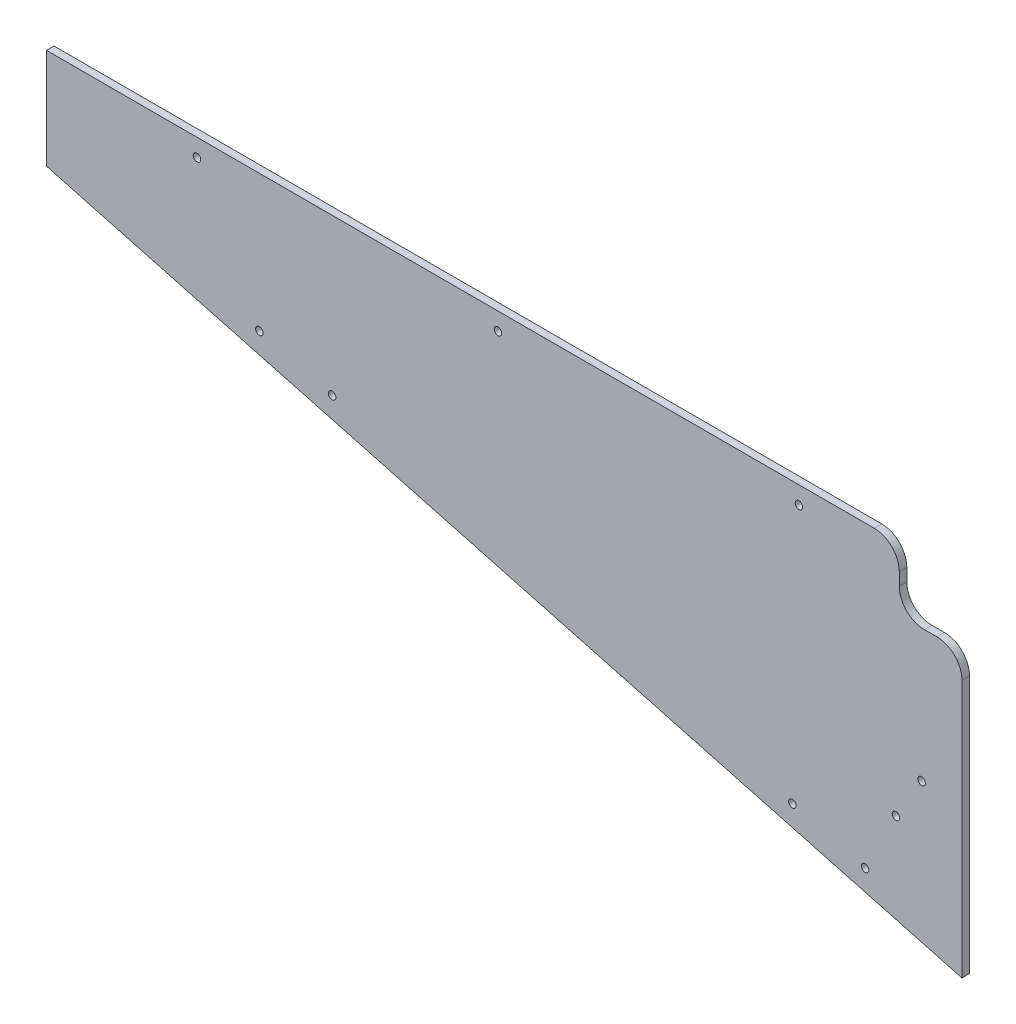
SolidWorks part; units mm, degrees
material "环氧树脂,未充填"
ref_plane "前视基准面" through (0, 0, 0) normal (0, 0, 1) x (1, 0, 0)
ref_plane "上视基准面" through (0, 0, 0) normal (0, 1, 0) x (1, 0, 0)
ref_plane "右视基准面" through (0, 0, 0) normal (1, 0, 0) x (0, 0, -1)
sketch "草图1" plane through (0, 0, 0) normal (0, 0, 1) x (1, 0, 0)
  line L0 (0, 0) -> (-514.282, 0)
  line L1 (-514.282, 0) -> (0, -137.8015)
  line L2 (0, -137.8015) -> (0, 0)
  line L3 (-365, 0) -> (-365, -40) construction
  line L4 (-365, 0) -> (-365, -40)
  dimension "D1" = 15
  dimension "D2" = 365
  dimension "D3" = 40
extrude "凸台-拉伸1" add sketch "草图1" along normal blind 3 contours L0 L4 L1 L2
sketch "草图3" plane through (0, 0, 3) normal (0, 0, 1) x (1, 0, 0)
  line L1 (0, 0) -> (-25, 0)
  line L2 (0, 0) -> (0, -25)
  line L3 (0, -25) -> (-25, -25)
  line L4 (-25, 0) -> (-25, -25)
  dimension "D1" = 25
  dimension "D2" = 25
extrude "切除-拉伸1" cut sketch "草图3" against normal through all
sketch "草图5" plane through (0, 0, 3) normal (0, 0, 1) x (1, 0, 0)
  line L0 (-376.077, -7) -> (-25, -7) construction
  line L2 (-25, 0) -> (-25, -25) construction
  line L3 (-25, 0) -> (-365, 0) construction
  circle A0 centre (-305, -7) radius 1.5
  circle A1 centre (-185, -7) radius 1.5
  circle A2 centre (-65, -7) radius 1.5
  dimension "D1" = 3
  dimension "D2" = 40
  dimension "D4" = 120
  dimension "D5" = 7
  dimension "D3" = 3
extrude "切除-拉伸3" cut sketch "草图5" against normal through all
fillet "圆角2" radius 10 3 edges at (0, -25, 1.5) (-25, -25, 1.5) (-25, 0, 1.5)
sketch "草图6" plane through (0, 0, 3) normal (0, 0, 1) x (1, 0, 0)
  line L0 (-483.3724, 0) -> (0, -129.5192) construction
  line L1 (-365, -40) -> (0, -137.8015) construction
  line L2 (0, -137.8015) -> (0, -35) construction
  line L3 (-35, 0) -> (-365, 0) construction
  circle A0 centre (-38.637, -119.1665) radius 1.5
  circle A1 centre (-67.6148, -111.4019) radius 1.5
  circle A2 centre (-251.1407, -62.2263) radius 1.5
  circle A3 centre (-280.1185, -54.4617) radius 1.5
  dimension "D2" = 30
  dimension "D3" = 3
  dimension "D5" = 30
  dimension "D1" = 8
  dimension "D4" = 40
  dimension "D6" = 190
extrude "切除-拉伸6" cut sketch "草图6" against normal blind 10
sketch "草图7" plane through (0, 0, 3) normal (0, 0, 1) x (1, 0, 0)
  line L0 (-26.327, -95.0301) -> (-35.2563, -128.3546) construction
  line L1 (-365, -40) -> (0, -137.8015) construction
  line L2 (-26.327, -95.0301) -> (-16.0862, -77.8509) construction
  line L3 (0, -137.8015) -> (0, -35) construction
  circle A0 centre (-26.327, -95.0301) radius 1.5
  circle A2 centre (-16.0862, -77.8509) radius 1.5
  dimension "D1" = 36.5
  dimension "D3" = 3
  dimension "D6" = 3
  dimension "D2" = 34.5
  dimension "D4" = 30.8
  dimension "D5" = 20
extrude "切除-拉伸7" cut sketch "草图7" against normal through all
